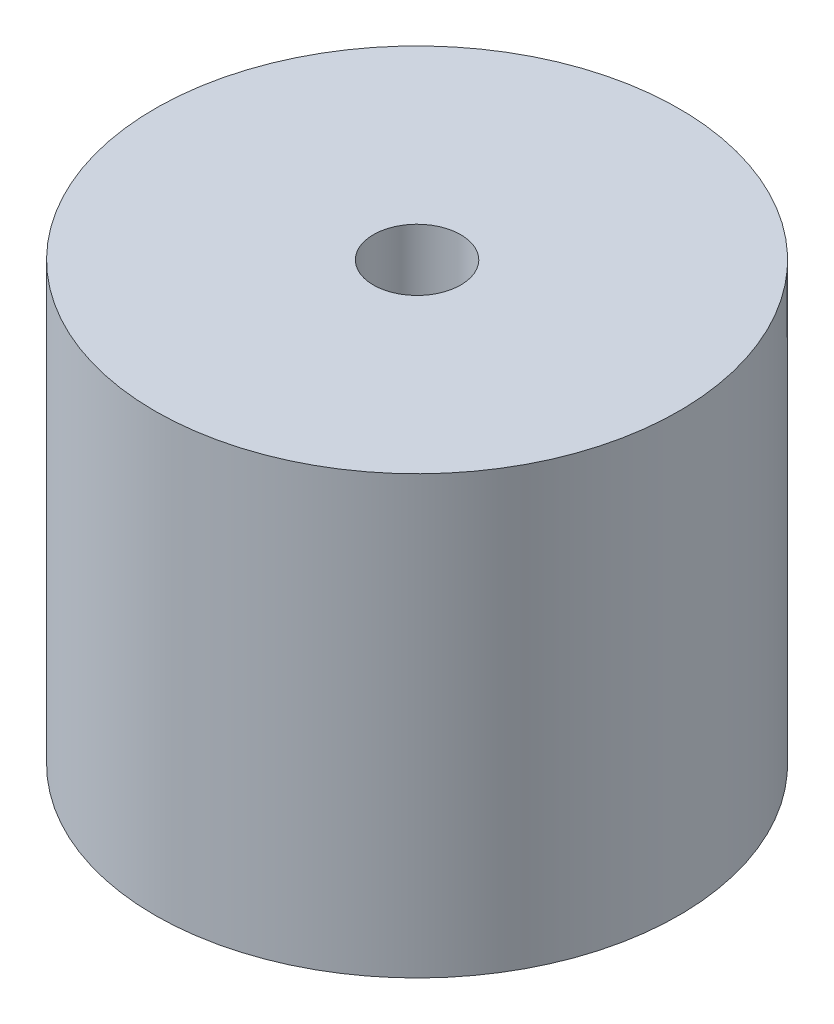
SolidWorks part; units mm, degrees
ref_plane "Front Plane" through (0, 0, 0) normal (0, 0, 1) x (1, 0, 0)
ref_plane "Top Plane" through (0, 0, 0) normal (0, 1, 0) x (1, 0, 0)
ref_plane "Right Plane" through (0, 0, 0) normal (1, 0, 0) x (0, 0, -1)
sketch "Sketch1" plane through (0, 0, 0) normal (0, 1, 0) x (1, 0, 0)
  circle A0 centre (0, 0) radius 18
  dimension "D1" = 36
extrude "Boss-Extrude1" add sketch "Sketch1" along normal blind 30
sketch "Sketch2" plane through (0, 30, 0) normal (0, 1, 0) x (1, 0, 0)
  circle A0 centre (0, 0) radius 3
  dimension "D1" = 6
extrude "Cut-Extrude1" cut sketch "Sketch2" against normal mid plane 85 contours A0
